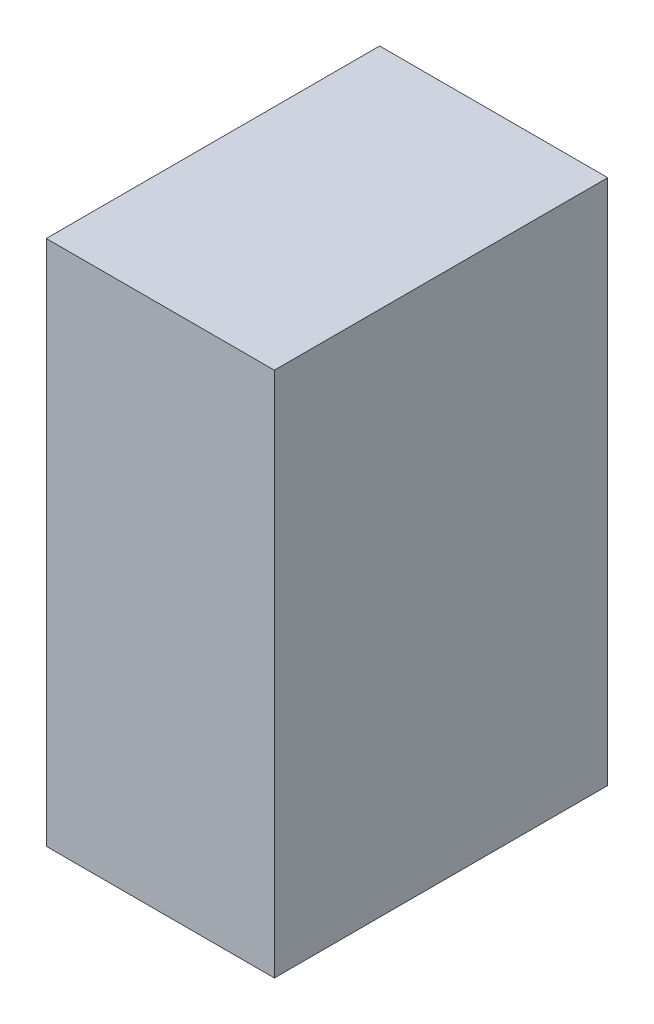
SolidWorks part; units mm, degrees
ref_plane "Front Plane" through (0, 0, 0) normal (1, 0, 0) x (0, 1, 0)
ref_plane "Top Plane" through (0, 0, 0) normal (0, 0, 1) x (0, 1, 0)
ref_plane "Right Plane" through (0, 0, 0) normal (0, 1, 0) x (-1, 0, 0)
sketch "Sketch1" plane through (0, 0, 0) normal (1, 0, 0) x (0, 1, 0)
  line L1 (0, 0) -> (150, 0)
  line L2 (0, 0) -> (0, 95)
  line L3 (0, 95) -> (150, 95)
  line L4 (150, 0) -> (150, 95)
  dimension "D1" = 95
  dimension "D2" = 150
extrude "Boss-Extrude1" add sketch "Sketch1" against normal blind 32.5
mirror "Mirror1" about plane through (0, 0, 0) normal (-1, 0, 0) of bodies 101
